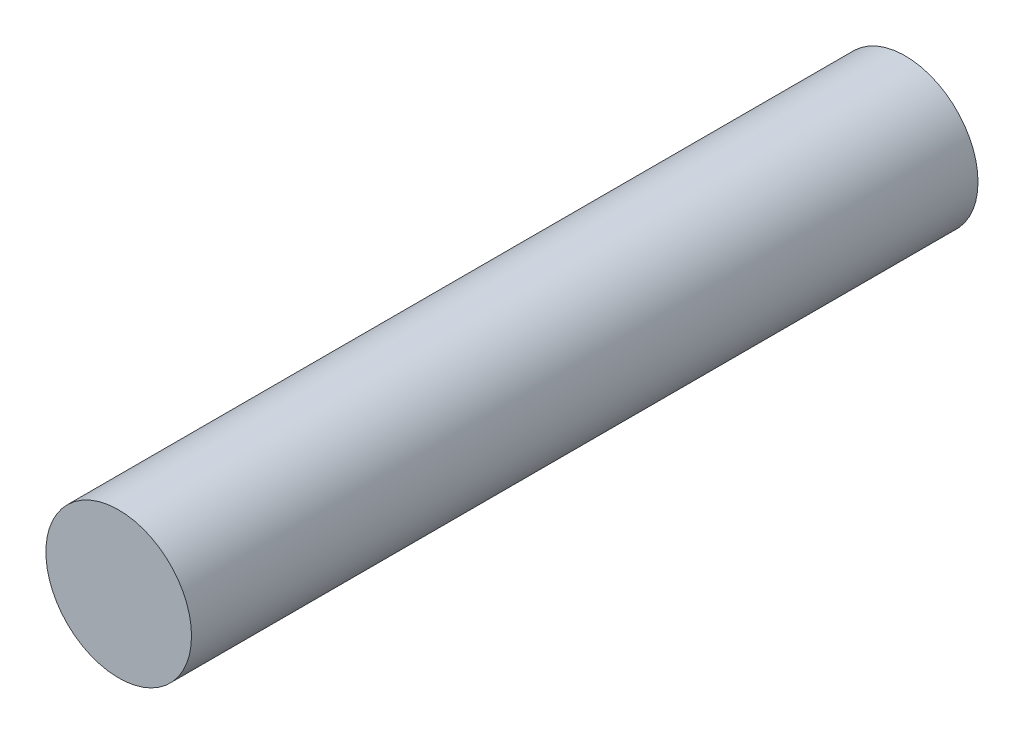
SolidWorks part; units mm, degrees
ref_plane "前视基准面" through (0, 0, 0) normal (0, 0, 1) x (1, 0, 0)
ref_plane "上视基准面" through (0, 0, 0) normal (0, 1, 0) x (1, 0, 0)
ref_plane "右视基准面" through (0, 0, 0) normal (1, 0, 0) x (0, 0, -1)
other "Configuration Table"
sketch "草图1" plane through (0, 0, 0) normal (0, 0, 1) x (1, 0, 0)
  circle A0 centre (0, 0) radius 2.5
  dimension "D1" = 5
extrude "凸台-拉伸1" add sketch "草图1" along normal blind 27
